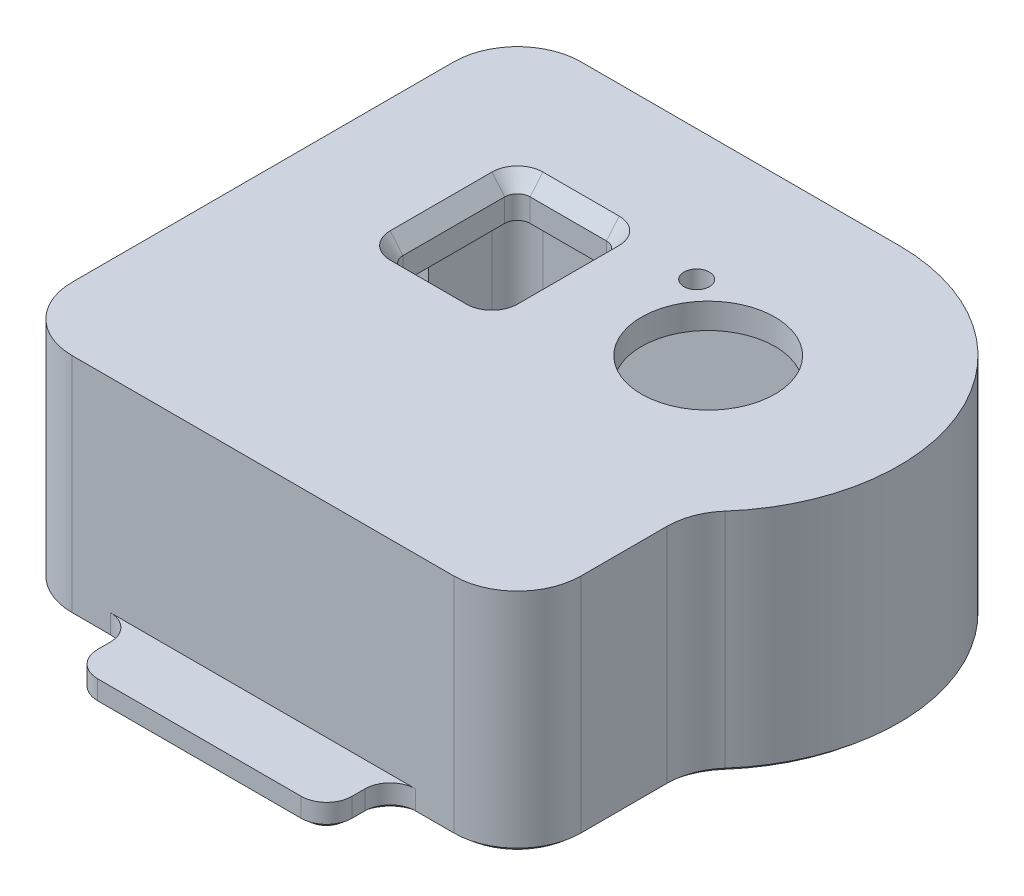
SolidWorks part; units mm, degrees
ref_plane "Front Plane" through (0, 0, 0) normal (0, 0, 1) x (1, 0, 0)
ref_plane "Top Plane" through (0, 0, 0) normal (0, 1, 0) x (1, 0, 0)
ref_plane "Right Plane" through (0, 0, 0) normal (1, 0, 0) x (0, 0, -1)
sketch "Sketch1" plane through (0, 0, 0) normal (0, 1, 0) x (1, 0, 0)
  line L5 (0, 15) -> (-30, 15)
  line L7 (10, -25) -> (-30, -25)
  line L8 (-30, 15) -> (-30, -25)
  line L9 (10, -11.1803) -> (10, -25)
  arc A0 (0, 15) -> (10, -11.1803) centre (0, 0) cw
  dimension "D3" = 15
  dimension "D1" = 40
  dimension "D2" = 40
  dimension "D4" = 10
extrude "Boss-Extrude1" add sketch "Sketch1" along normal blind 18
fillet "Fillet1" radius 5 3 edges at (-30, 9, 25) (-30, 9, -15) (10, 9, 25)
shell "Shell1" thickness 3
sketch "Sketch3" plane through (0, 18, 0) normal (0, 1, 0) x (1, 0, 0)
  circle A0 centre (0, 0) radius 5.25
  dimension "D1" = 10.5
extrude "Cut-Extrude1" cut sketch "Sketch3" against normal through all
sketch "Sketch4" plane through (0, 15, 0) normal (0, -1, 0) x (1, 0, 0)
  circle A0 centre (0, 0) radius 11.5
  dimension "D1" = 23
extrude "Cut-Extrude2" cut sketch "Sketch4" against normal offset from surface (1 mm away) 2 contours A0 up to face at (0, 18, 5.25)
sketch "Sketch5" plane through (0, 18, 0) normal (0, 1, 0) x (1, 0, 0)
  line L3 (-5.6457, 4.7373) -> (0, 0) construction
  line L5 (0, 0) -> (5.25, 0) construction
  circle A0 centre (-5.6457, 4.7373) radius 1
  circle A1 centre (0, 0) radius 5.25 construction
  dimension "D3" = 2
  dimension "D1" = 140
  dimension "D2" = 7.37
extrude "Cut-Extrude3" cut sketch "Sketch5" against normal through all
sketch "Sketch6" plane through (-30, 0, 0) normal (-1, 0, 0) x (0, 0, 1)
  line L0 (-10, 0) -> (20, 0) construction
  line L1 (-5, 0) -> (5, 0)
  line L2 (-5, 0) -> (-5, 10)
  line L3 (-5, 10) -> (5, 10)
  line L4 (5, 0) -> (5, 10)
  dimension "D1" = 10
  dimension "D2" = 10
extrude "Cut-Extrude4" cut sketch "Sketch6" against normal up to next
fillet "Fillet2" radius 1 2 edges at (-28.5, 10, 5) (-28.5, 10, -5)
sketch "Sketch7" plane through (0, 18, 0) normal (0, 1, 0) x (1, 0, 0)
  line L0 (-12, 0) -> (0, 0) construction
  line L1 (-20, 5) -> (-12, 5)
  line L2 (-20, 5) -> (-20, -5)
  line L3 (-20, -5) -> (-12, -5)
  line L4 (-12, 5) -> (-12, -5)
  dimension "D1" = 10
  dimension "D2" = 8
  dimension "D3" = 12
extrude "Cut-Extrude7" cut sketch "Sketch7" against normal up to next
fillet "Fillet3" radius 1 4 edges at (-12, 16.5, -5) (-12, 16.5, 5) (-20, 16.5, 5) (-20, 16.5, -5)
sketch "Sketch8" plane through (0, 0, 0) normal (0, -1, 0) x (1, 0, 0)
  line L0 (-20, 25) -> (0, 25)
  line L1 (-25, 25) -> (5, 25) construction
  line L2 (0, 25) -> (0, 30)
  line L3 (0, 30) -> (-20, 30)
  line L4 (-20, 30) -> (-20, 25)
  line L5 (10, 25) -> (-30, 25) construction
  line L6 (0, -15) -> (-30, -15) construction
  line L7 (-22.5, -20) -> (-7.5, -20)
  line L8 (-22.5, -20) -> (-22.5, -15)
  line L9 (-22.5, -15) -> (-7.5, -15)
  line L10 (-7.5, -20) -> (-7.5, -15)
  point P4 (-15, -15)
  point P8 (-10, 25)
  dimension "D1" = 20
  dimension "D2" = 5
  dimension "D3" = 15
  dimension "D4" = 5
extrude "Boss-Extrude2" add sketch "Sketch8" against normal blind 2
fillet "Fillet4" radius 2 8 edges at (-22.5, 1, -20) (-7.5, 1, -20) (-22.5, 1, -15) (-7.5, 1, -15) (0, 1, 25) (0, 1, 30) (-20, 1, 30) (-20, 1, 25)
fillet "Fillet5" radius 5 1 edges at (10, 9, 11.1803)
fillet "Fillet6" radius 5 1 edges at (7, 7.5, 9.7468)
chamfer "Chamfer2" distance 1 angle 50 8 edges at (-12, 18, 0) (-12.2929, 18, -4.7071) (-12.2929, 18, 4.7071) (-16, 18, -5) (-16, 18, 5) (-19.7071, 18, -4.7071) (-19.7071, 18, 4.7071) (-20, 18, 0)
chamfer "Chamfer3" distance 0.5 angle 50 36 edges at (-27, 0, 12.5) (-26.4142, 0, 21.4142) (-10, 0, 22) (6.4142, 0, 21.4142) (7, 0, 16.0208) (7.3823, 0, 10.1242) (-27, 0, -7.5) (11.0905, 0, -4.5826) (-26.4142, 0, -11.4142) (-12.5, 0, -12) (-30, 0, -7.5) (-28.5355, 0, -13.5355) (-24.75, 0, -15) (-23.0858, 0, -15.5858) (-30, 0, 12.5) (-22.5, 0, -17.5) (-28.5355, 0, 23.5355) (-21.9142, 0, -19.4142) (-23.5, 0, 25) (-15, 0, -20) (-20.5858, 0, 25.5858) (-8.0858, 0, -19.4142) (-20, 0, 27.5) (-7.5, 0, -17.5) (-19.4142, 0, 29.4142) (-6.9142, 0, -15.5858) (-10, 0, 30) (-2.75, 0, -15) (-0.5858, 0, 29.4142) (13.6716, 0, -6.1716) (0, 0, 27.5) (10.3229, 0, 11.461) (0.5858, 0, 25.5858) (10, 0, 16.6144) (3.5, 0, 25) (8.5355, 0, 23.5355)
